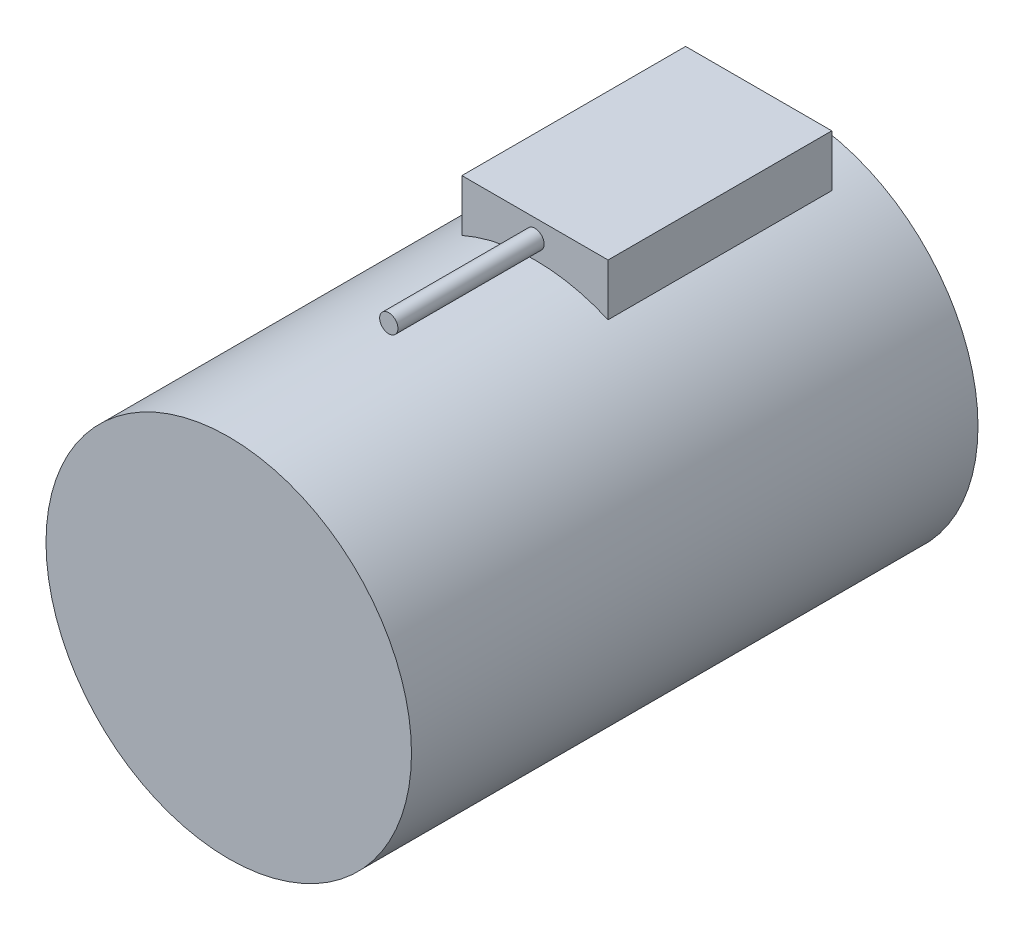
SolidWorks part; units mm, degrees
ref_plane "Front Plane" through (0, 0, 0) normal (0, 0, 1) x (1, 0, 0)
ref_plane "Top Plane" through (0, 0, 0) normal (0, 1, 0) x (1, 0, 0)
ref_plane "Right Plane" through (0, 0, 0) normal (1, 0, 0) x (0, 0, -1)
sketch "Sketch7" plane through (0, 0, 0) normal (0, 0, 1) x (1, 0, 0)
  circle A0 centre (0, 0) radius 63.5
  dimension "D1" = 127
extrude "Boss-Extrude4" add sketch "Sketch7" along normal blind 196.85
ref_plane "Plane1" through (0, 50.8, 0) normal (0, 1, 0) x (1, 0, 0)
sketch "Sketch9" plane through (0, 50.8, 0) normal (0, 1, 0) x (1, 0, 0)
  line L0 (-63.5, 0) -> (-63.5, -196.85) construction
  line L1 (-25.4, -12.7) -> (25.4, -12.7)
  line L2 (-25.4, -12.7) -> (-25.4, -90.4392)
  line L3 (-25.4, -90.4392) -> (25.4, -90.4392)
  line L4 (25.4, -12.7) -> (25.4, -90.4392)
  line L5 (63.5, -196.85) -> (63.5, 0) construction
  line L6 (63.5, 0) -> (-63.5, 0) construction
  dimension "D1" = 38.1
  dimension "D2" = 38.1
  dimension "D3" = 12.7
extrude "Boss-Extrude5" add sketch "Sketch9" along normal blind 25.4
sketch "Sketch10" plane through (0, 0, 90.4392) normal (0, 0, 1) x (1, 0, 0)
  line L0 (-25.4, 76.2) -> (25.4, 76.2) construction
  line L1 (-25.4, 76.2) -> (-25.4, 58.1987) construction
  circle A0 centre (0, 69.85) radius 3.175
  dimension "D1" = 6.35
  dimension "D2" = 6.35
  dimension "D3" = 25.4
extrude "Boss-Extrude6" add sketch "Sketch10" along normal blind 50.8
